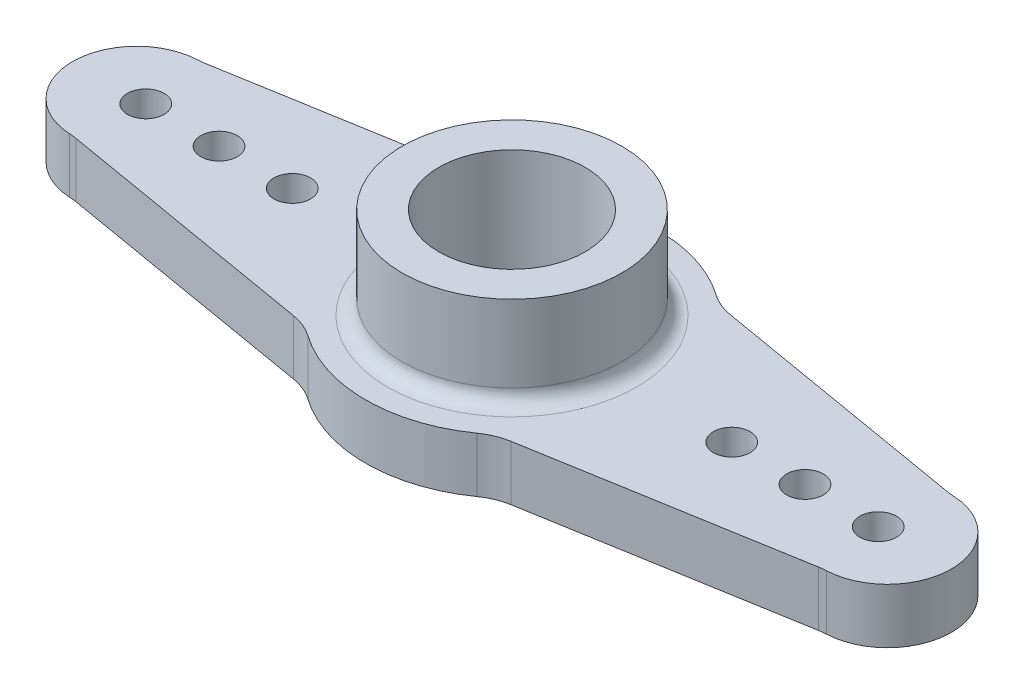
SolidWorks part; units mm, degrees
material "ABS"
ref_plane "Front Plane" through (0, 0, 0) normal (0, 0, 1) x (1, 0, 0)
ref_plane "Top Plane" through (0, 0, 0) normal (0, 1, 0) x (1, 0, 0)
ref_plane "Right Plane" through (0, 0, 0) normal (1, 0, 0) x (0, 0, -1)
sketch "Sketch1" plane through (0, 0, 0) normal (0, 1, 0) x (1, 0, 0)
  line L6 (4.0892, 4.8581) -> (16.2719, 2.7781)
  line L8 (16.2719, -2.7781) -> (4.0892, -4.8581)
  line L10 (-16.2719, 2.7781) -> (-4.0892, 4.8581)
  line L11 (-4.0892, -4.8581) -> (-16.2719, -2.7781)
  arc A0 (4.0892, 4.8581) -> (-4.0892, 4.8581) centre (0, 0) ccw
  arc A1 (16.2719, -2.7781) -> (16.2719, 2.7781) centre (16.2719, 0) ccw
  arc A2 (-16.2719, 2.7781) -> (-16.2719, -2.7781) centre (-16.2719, 0) ccw
  arc A5 (-4.0892, -4.8581) -> (4.0892, -4.8581) centre (0, 0) ccw
  dimension "D1" = 12.7
  dimension "D4" = 5.5562
  dimension "D5" = 5.5562
extrude "Boss-Extrude1" add sketch "Sketch1" along normal blind 2.3813
fillet "Fillet1" radius 2.54 4 edges at (-16.2719, 1.1906, -2.7781) (-16.2719, 1.1906, 2.7781) (16.2719, 1.1906, -2.7781) (16.2719, 1.1906, 2.7781)
fillet "Fillet2" radius 2.54 4 edges at (4.0892, 1.1906, -4.8581) (-4.0892, 1.1906, -4.8581) (4.0892, 1.1906, 4.8581) (-4.0892, 1.1906, 4.8581)
sketch "Sketch2" plane through (0, 2.3813, 0) normal (0, 1, 0) x (1, 0, 0)
  circle A0 centre (0, 0) radius 4.7625
  dimension "D1" = 9.525
extrude "Boss-Extrude2" add sketch "Sketch2" along normal blind 3.9688
fillet "Fillet3" radius 0.635 1 edges at (0, 2.3813, 4.7625)
sketch "Sketch3" plane through (0, 6.35, 0) normal (0, 1, 0) x (1, 0, 0)
  circle A0 centre (0, 0) radius 3.175
  dimension "D1" = 6.35
extrude "Cut-Extrude1" cut sketch "Sketch3" against normal blind 6.35
sketch "Sketch4" plane through (0, 2.3813, 0) normal (0, 1, 0) x (1, 0, 0)
  circle A0 centre (9.525, 0) radius 0.7937
  circle A1 centre (-9.525, 0) radius 0.7937
  circle A3 centre (12.7, 0) radius 0.7937
  circle A4 centre (15.875, 0) radius 0.7937
  circle A5 centre (-12.7, 0) radius 0.7937
  circle A6 centre (-15.875, 0) radius 0.7937
  dimension "D3" = 1.5875
  dimension "D4" = 1.5875
  dimension "D5" = 1.5875
  dimension "D6" = 1.5875
  dimension "D7" = 1.5875
  dimension "D8" = 1.5875
  dimension "D9" = 3.175
  dimension "D10" = 3.175
  dimension "D11" = 3.175
  dimension "D1" = 9.525
  dimension "D2" = 19.05
  dimension "D12" = 3.175
extrude "Cut-Extrude2" cut sketch "Sketch4" against normal blind 6.35
